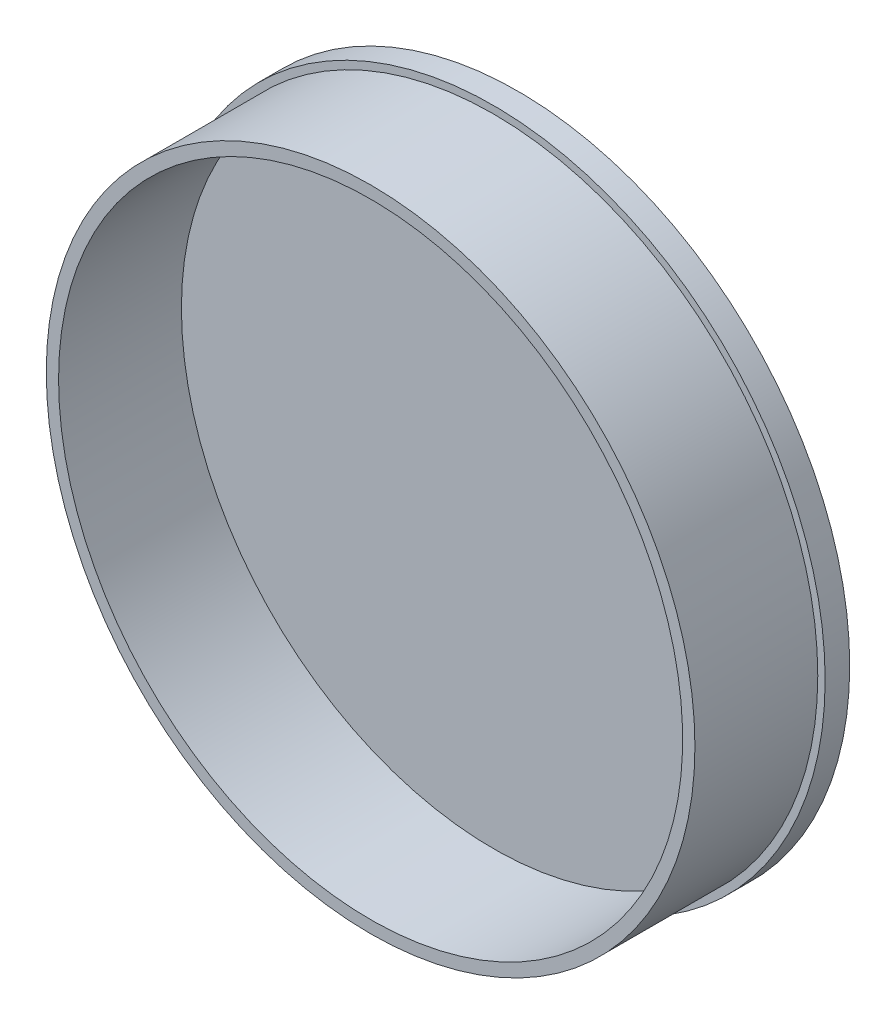
SolidWorks part; units mm, degrees
ref_plane "Front Plane" through (0, 0, 0) normal (0, 0, 1) x (1, 0, 0)
ref_plane "Top Plane" through (0, 0, 0) normal (0, 1, 0) x (1, 0, 0)
ref_plane "Right Plane" through (0, 0, 0) normal (1, 0, 0) x (0, 0, -1)
sketch "Sketch1" plane through (0, 0, 0) normal (0, 0, 1) x (1, 0, 0)
  circle A0 centre (0, 0) radius 135
extrude "Boss-Extrude1" add sketch "Sketch1" along normal mid plane 10
sketch "Sketch2" plane through (0, 0, 5) normal (0, 0, 1) x (1, 0, 0)
  circle A0 centre (0, 0) radius 132
  circle A1 centre (0, 0) radius 127
extrude "Boss-Extrude2" add sketch "Sketch2" along normal blind 50
sketch "Sketch4" plane through (0, 0, 55) normal (0, 0, 1) x (1, 0, 0)
  line L0 (0, 132) -> (0, -132)
  circle A0 centre (0, 0) radius 132 construction
  point P7 (0, 0)
